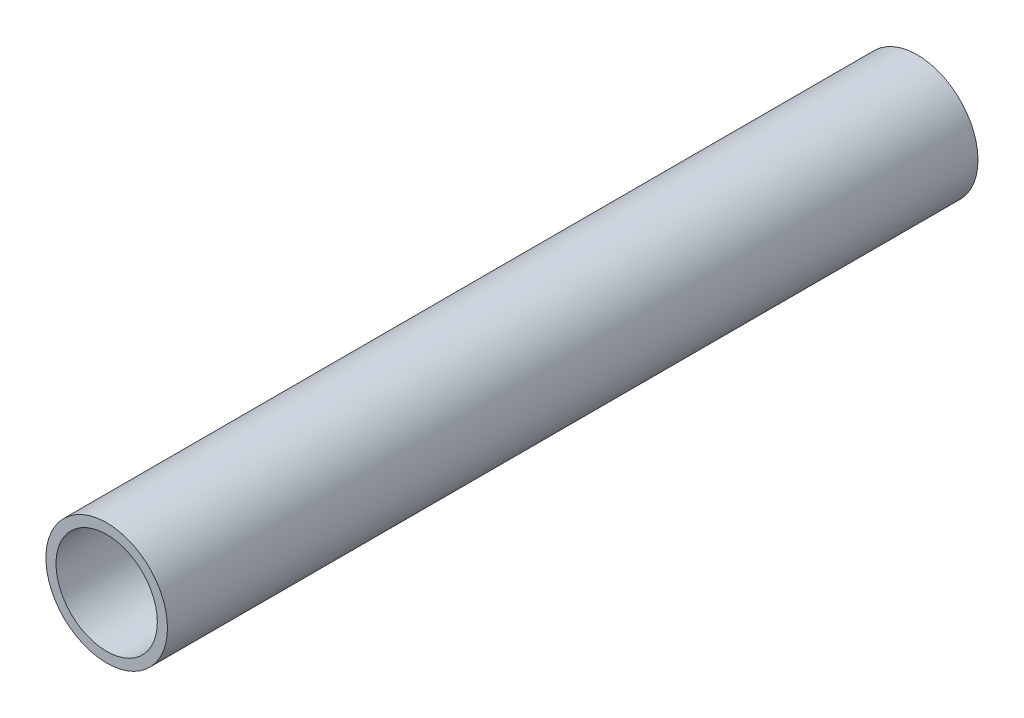
SolidWorks part; units mm, degrees
ref_plane "前视基准面" through (0, 0, 0) normal (0, 0, 1) x (1, 0, 0)
ref_plane "上视基准面" through (0, 0, 0) normal (0, 1, 0) x (1, 0, 0)
ref_plane "右视基准面" through (0, 0, 0) normal (1, 0, 0) x (0, 0, -1)
sketch "草图1" plane through (0, 0, 0) normal (0, 0, 1) x (1, 0, 0)
  circle A0 centre (0, 0) radius 5
  circle A1 centre (0, 0) radius 6
  dimension "D1" = 10
  dimension "D2" = 12
extrude "凸台-拉伸1" add sketch "草图1" along normal blind 80
